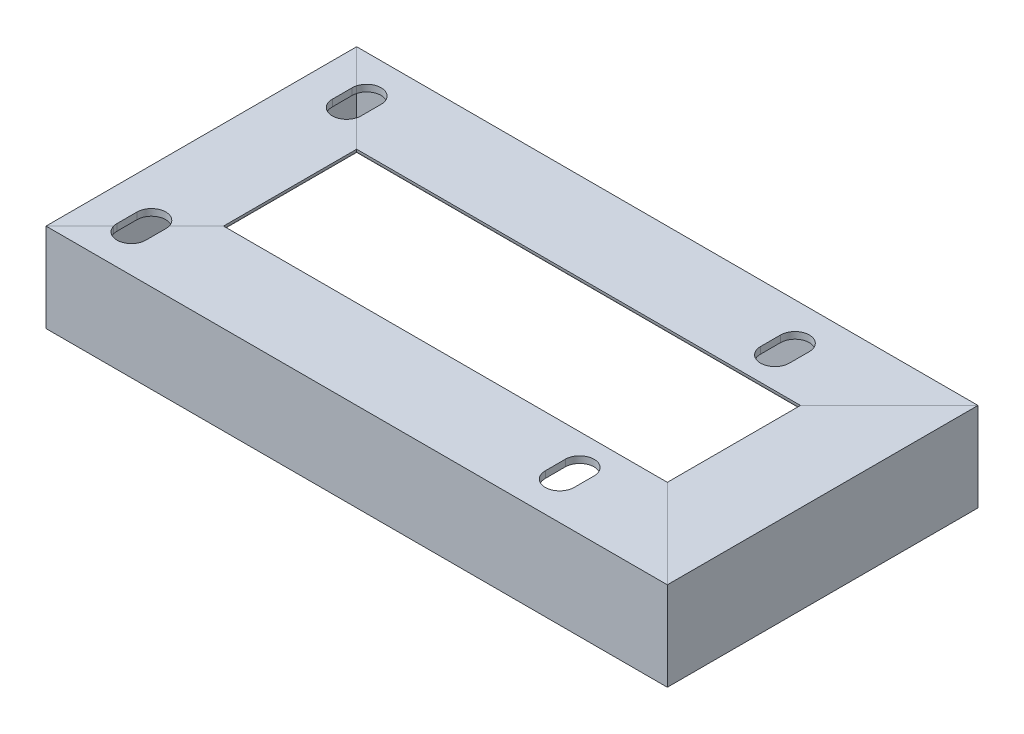
SolidWorks part; units mm, degrees
ref_plane "Front Plane" through (0, 0, 0) normal (0, 0, 1) x (1, 0, 0)
ref_plane "Top Plane" through (0, 0, 0) normal (0, 1, 0) x (1, 0, 0)
ref_plane "Right Plane" through (0, 0, 0) normal (1, 0, 0) x (0, 0, -1)
sketch3d "3DSketch2"
  line L1 (-140, 0, 70) -> (-140, 0, -70)
  line L2 (-140, 0, 70) -> (140, 0, 70)
  line L3 (140, 0, 70) -> (140, 0, -70)
  line L4 (-140, 0, -70) -> (140, 0, -70)
  line L5 (-140, 0, 70) -> (140, 0, -70) construction
  line L6 (140, 0, 70) -> (-140, 0, -70) construction
  point P0 (0, 0, 0)
  dimension "D1" = 140
  dimension "D2" = 280
other "Iron V40X40X3(1)"
ref_plane "Plane1" through (-140, 0, 70) normal (0, 0, -1) x (1, 0, 0)
sketch "Sketch1" plane through (-140, 0, 70) normal (0, 0, -1) x (1, 0, 0)
  line L0 (0, 0) -> (0, 40)
  line L1 (0, 20) -> (3, 20) construction
  line L2 (3, 37) -> (3, 6.5)
  line L3 (6.5, 3) -> (37, 3)
  line L4 (20, 3) -> (20, 0) construction
  line L5 (40, 0) -> (0, 0)
  arc A0 (40, 0) -> (37, 3) centre (37, 0) ccw
  arc A1 (0, 40) -> (3, 37) centre (0, 37) cw
  arc A2 (6.5, 3) -> (3, 6.5) centre (6.5, 6.5) cw
  point P10 (20, 0)
  point P14 (0, 20)
  point P15 (3, 20)
  point P16 (20, 3)
  point P17 (3, 40)
  point P18 (40, 3)
  point P21 (0, 0)
  dimension "D2" = 3
  dimension "D3" = 40
  dimension "Radius_1" = 3.5
  dimension "D1" = 3
sketch "Sketch2" plane through (0, 0, 0) normal (0, 1, 0) x (1, 0, 0)
  line L0 (74.5, 53) -> (74.5, 44) construction
  line L1 (81, 53) -> (81, 44)
  line L2 (68, 53) -> (68, 44)
  line L3 (-118.5, 53) -> (-118.5, 44) construction
  line L4 (-112, 53) -> (-112, 44)
  line L5 (-125, 53) -> (-125, 44)
  line L6 (-118.5, -44) -> (-118.5, -53) construction
  line L7 (-112, -44) -> (-112, -53)
  line L8 (-125, -44) -> (-125, -53)
  line L9 (74.5, -44) -> (74.5, -53) construction
  line L10 (81, -44) -> (81, -53)
  line L11 (68, -44) -> (68, -53)
  line L12 (140, -70) -> (140, 70) construction
  line L13 (140, 70) -> (-140, 70) construction
  arc A0 (81, 53) -> (68, 53) centre (74.5, 53) ccw
  arc A1 (68, 44) -> (81, 44) centre (74.5, 44) ccw
  arc A2 (-112, 53) -> (-125, 53) centre (-118.5, 53) ccw
  arc A3 (-125, 44) -> (-112, 44) centre (-118.5, 44) ccw
  arc A4 (-112, -44) -> (-125, -44) centre (-118.5, -44) ccw
  arc A5 (-125, -53) -> (-112, -53) centre (-118.5, -53) ccw
  arc A6 (81, -44) -> (68, -44) centre (74.5, -44) ccw
  arc A7 (68, -53) -> (81, -53) centre (74.5, -53) ccw
  point P2 (74.5, 48.5)
  point P12 (-118.5, 48.5)
  point P19 (-118.5, -48.5)
  point P26 (74.5, -48.5)
  dimension "D6" = 17
  dimension "D1" = 9
  dimension "D2" = 13
  dimension "D5" = 65.5
  dimension "D3" = 2
  dimension "D4" = 2
extrude "Cut-Extrude1" cut sketch "Sketch2" against normal blind 10
